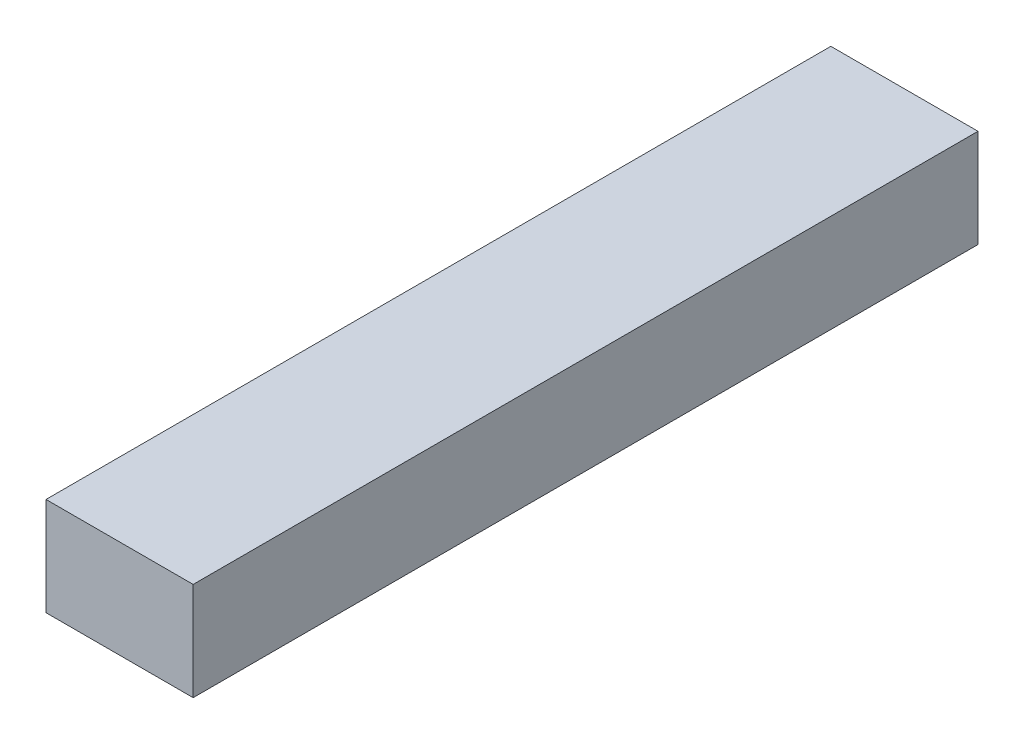
SolidWorks part; units mm, degrees
ref_plane "Ebene vorne" through (0, 0, 0) normal (0, 0, 1) x (1, 0, 0)
ref_plane "Ebene oben" through (0, 0, 0) normal (0, 1, 0) x (1, 0, 0)
ref_plane "Ebene rechts" through (0, 0, 0) normal (1, 0, 0) x (0, 0, -1)
sketch "Skizze1" plane through (0, 0, 0) normal (0, 1, 0) x (1, 0, 0)
  line L1 (0, 0) -> (15, 0)
  line L2 (0, 0) -> (0, 80)
  line L3 (0, 80) -> (15, 80)
  line L4 (15, 0) -> (15, 80)
  line L5 (0, 0) -> (15, 80) construction
  line L6 (0, 80) -> (15, 0) construction
  point P4 (7.5, 40)
  dimension "D1" = 80
  dimension "D2" = 15
extrude "Aufsatz-Linear austragen1" add sketch "Skizze1" along normal blind 10
